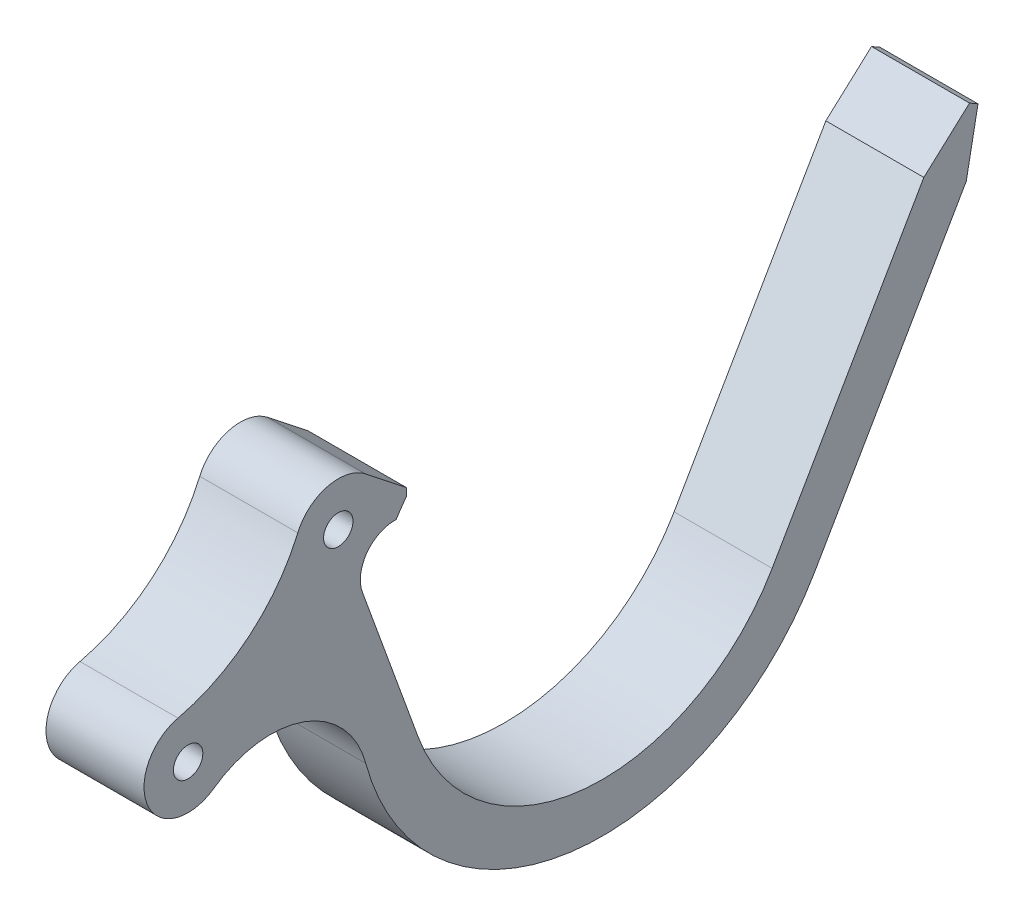
SolidWorks part; units mm, degrees
ref_plane "前视基准面" through (0, 0, 0) normal (0, 0, 1) x (1, 0, 0)
ref_plane "上视基准面" through (0, 0, 0) normal (0, 1, 0) x (1, 0, 0)
ref_plane "右视基准面" through (0, 0, 0) normal (1, 0, 0) x (0, 0, -1)
other "Configuration Table"
sketch "草图1" plane through (0, 0, 0) normal (1, 0, 0) x (0, 0, -1)
  line L0 (-25, 0) -> (25, 0)
  line L1 (-20, 0) -> (-20, 23.9009)
  line L2 (0, 0) -> (-18.7939, -6.8404)
  line L3 (-18.7939, -6.8404) -> (-31.5665, 28.2521)
  line L4 (-61.1517, 35.306) -> (21.6506, -12.5)
  line L5 (-26.9459, 15.5572) -> (-42.2668, 2.7015)
  line L6 (-24.156, 19.088) -> (-15.6921, 12.3999)
  line L7 (-21.1966, 13.4944) -> (-21.0452, 13.4944)
  line L8 (-26.9459, 15.5572) -> (78.2827, 15.5572)
  line L9 (-34.6064, 9.1294) -> (-47.3799, 24.3523)
  line L10 (21.6506, -12.5) -> (37.1278, 14.3072)
  line L11 (37.1278, 14.3072) -> (32.7977, 16.8072)
  line L12 (32.7977, 16.8072) -> (17.3205, -10)
  line L13 (32.7977, 16.8072) -> (37.4576, 21.0443)
  line L14 (37.4576, 21.0443) -> (38.3237, 20.5443)
  line L15 (38.3237, 20.5443) -> (37.1278, 14.3072)
  line L16 (37.8906, 20.7943) -> (34.9627, 15.5572)
  circle A0 centre (0, 0) radius 25
  circle A1 centre (0, 0) radius 20
  circle A2 centre (-26.9459, 15.5572) radius 1.5
  circle A3 centre (-26.9459, 15.5572) radius 4.5
  circle A4 centre (-42.2668, 2.7015) radius 1.5
  circle A5 centre (-42.2668, 2.7015) radius 4.5
  circle A6 centre (-21.1966, 9.9944) radius 3.5
  circle A7 centre (-47.3799, 24.3523) radius 17.7463
  circle A8 centre (-33.8156, -9.1058) radius 10.0202
  point P33 (34.9627, 15.5572)
  point P38 (-32.2081, -7.5244)
  point P39 (-30.9298, -4.6932)
  point P40 (-34.4614, -7.5244)
  dimension "D1" = 50
  dimension "D2" = 5
  dimension "D5" = 3
  dimension "D7" = 9
  dimension "D8" = 7
  dimension "D3" = 20
  dimension "D4" = 30
  dimension "D6" = 40
  dimension "D9" = 20
  dimension "D10" = 1
  dimension "D11" = 6
extrude "凸台-拉伸2" add sketch "草图1" along normal blind 10
